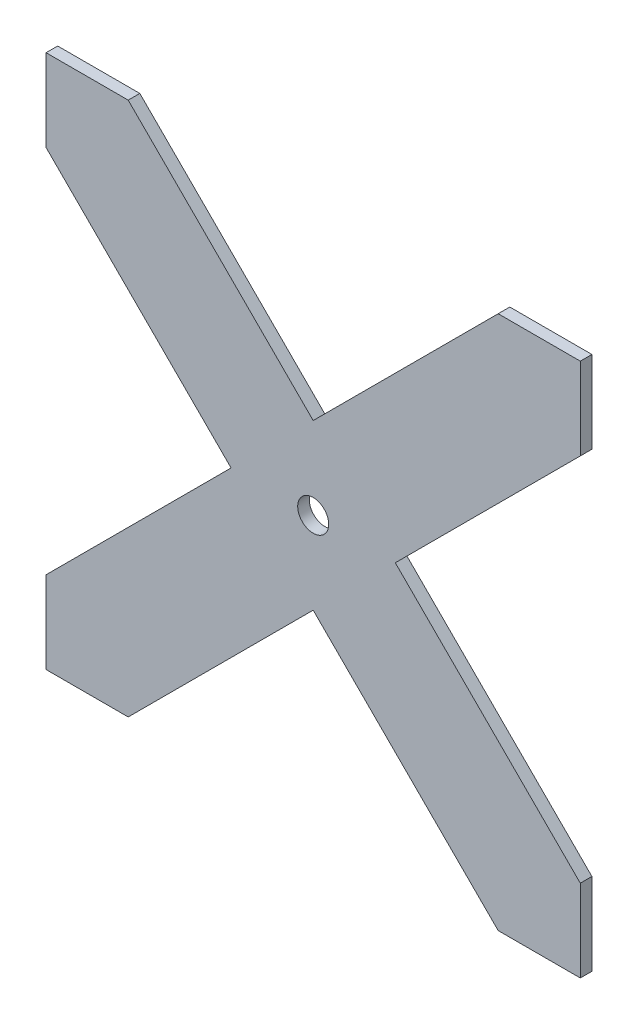
SolidWorks part; units mm, degrees
ref_plane "Front Plane" through (0, 0, 0) normal (0, 0, 1) x (1, 0, 0)
ref_plane "Top Plane" through (0, 0, 0) normal (0, 1, 0) x (1, 0, 0)
ref_plane "Right Plane" through (0, 0, 0) normal (1, 0, 0) x (0, 0, -1)
sketch "Sketch7" plane through (0, 0, 0) normal (0, 0, 1) x (1, 0, 0)
  line L0 (-78.549, 130.1171) -> (38.2378, 13.3303)
  line L1 (-99.7622, 130.1171) -> (38.2378, 130.1171) construction
  line L4 (38.2378, -7.8829) -> (-99.7622, -7.8829) construction
  line L6 (-99.7622, -7.8829) -> (-99.7622, 130.1171) construction
  line L9 (17.0246, -7.8829) -> (38.2378, -7.8829)
  line L11 (17.0246, -7.8829) -> (-99.7622, 108.9039)
  line L12 (-78.549, 130.1171) -> (-99.7622, 130.1171)
  line L15 (38.2378, 130.1171) -> (38.2378, -7.8829) construction
  line L16 (-99.7622, 130.1171) -> (-99.7622, 108.9039)
  line L17 (38.2378, -7.8829) -> (38.2378, 13.3303)
  line L18 (-20.1556, 71.7237) -> (-41.3688, 50.5105) construction
  point P15 (-30.7622, 130.1171)
  point P20 (-30.7622, 61.1171)
  point P21 (38.2378, 61.1171)
  dimension "D1" = 30
extrude "Boss-Extrude1" add sketch "Sketch7" along normal blind 3
sketch "Sketch8" plane through (0, 0, 0) normal (0, 0, 1) x (1, 0, 0)
  line L0 (-78.549, -7.8829) -> (38.2378, 108.9039)
  line L1 (-99.7622, -7.8829) -> (38.2378, -7.8829) construction
  line L4 (38.2378, 130.1171) -> (-99.7622, 130.1171) construction
  line L6 (-99.7622, 130.1171) -> (-99.7622, -7.8829) construction
  line L9 (17.0246, 130.1171) -> (38.2378, 130.1171)
  line L11 (17.0246, 130.1171) -> (-99.7622, 13.3303)
  line L12 (-78.549, -7.8829) -> (-99.7622, -7.8829)
  line L15 (38.2378, -7.8829) -> (38.2378, 130.1171) construction
  line L16 (-99.7622, -7.8829) -> (-99.7622, 13.3303)
  line L17 (38.2378, 130.1171) -> (38.2378, 108.9039)
  line L18 (-20.1556, 50.5105) -> (-41.3688, 71.7237) construction
  point P15 (-30.7622, -7.8829)
  point P20 (-30.7622, 61.1171)
  point P21 (38.2378, 61.1171)
  dimension "D1" = 30
extrude "Boss-Extrude2" add sketch "Sketch8" along normal blind 3
sketch "Sketch9" plane through (0, 0, 3) normal (0, 0, 1) x (1, 0, 0)
  line L0 (-99.7622, 130.1171) -> (-30.7622, 61.1171) construction
  line L1 (-30.7622, 61.1171) -> (38.2378, 130.1171) construction
  line L2 (-99.7622, -7.8829) -> (-30.7622, 61.1171) construction
  line L3 (-30.7622, 61.1171) -> (38.2378, -7.8829) construction
  circle A0 centre (-30.7622, 61.1171) radius 4
  dimension "D1" = 8
extrude "Cut-Extrude1" cut sketch "Sketch9" against normal through all both and the other way through all
